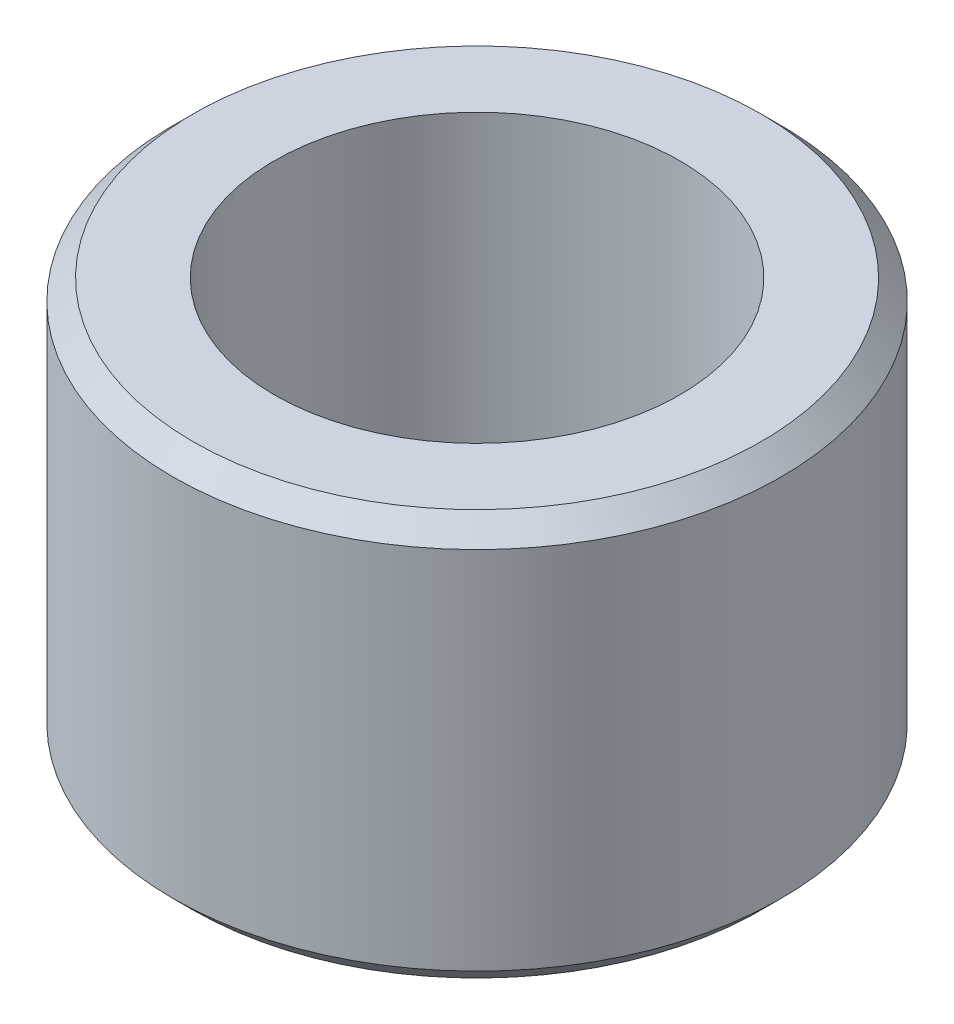
SolidWorks part; units mm, degrees
ref_plane "Front Plane" through (0, 0, 0) normal (0, 0, 1) x (1, 0, 0)
ref_plane "Top Plane" through (0, 0, 0) normal (0, 1, 0) x (1, 0, 0)
ref_plane "Right Plane" through (0, 0, 0) normal (1, 0, 0) x (0, 0, -1)
sketch "Sketch1" plane through (0, 0, 0) normal (0, 1, 0) x (1, 0, 0)
  circle A0 centre (0, 0) radius 15
  circle A1 centre (0, 0) radius 10
  dimension "D1" = 30
  dimension "D2" = 20
extrude "Boss-Extrude1" add sketch "Sketch1" along normal blind 20
chamfer "Chamfer1" distance 1 angle 45 2 edges at (0, 0, 15) (0, 20, 15)
